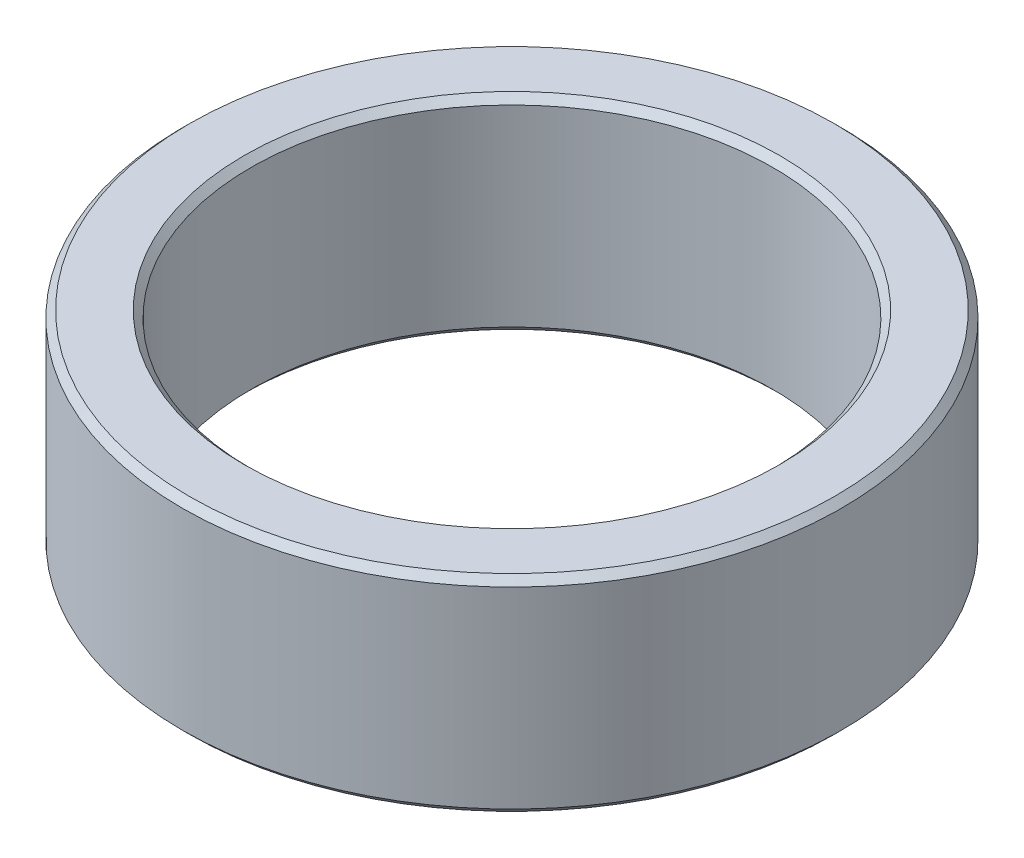
SolidWorks part; units mm, degrees
material "AISI 1010 Steel, hot rolled bar"
ref_plane "Front Plane" through (0, 0, 0) normal (0, 0, 1) x (1, 0, 0)
ref_plane "Top Plane" through (0, 0, 0) normal (0, 1, 0) x (1, 0, 0)
ref_plane "Right Plane" through (0, 0, 0) normal (1, 0, 0) x (0, 0, -1)
sketch "Sketch1" plane through (0, 0, 0) normal (0, 1, 0) x (1, 0, 0)
  circle A0 centre (0, 0) radius 19
  circle A1 centre (0, 0) radius 24
  dimension "D1" = 38
  dimension "D2" = 48
extrude "Boss-Extrude1" add sketch "Sketch1" along normal blind 15
chamfer "Chamfer1" distance 0.5 angle 45 4 edges at (0, 0, 19) (0, 0, 24) (0, 15, 19) (0, 15, 24)
